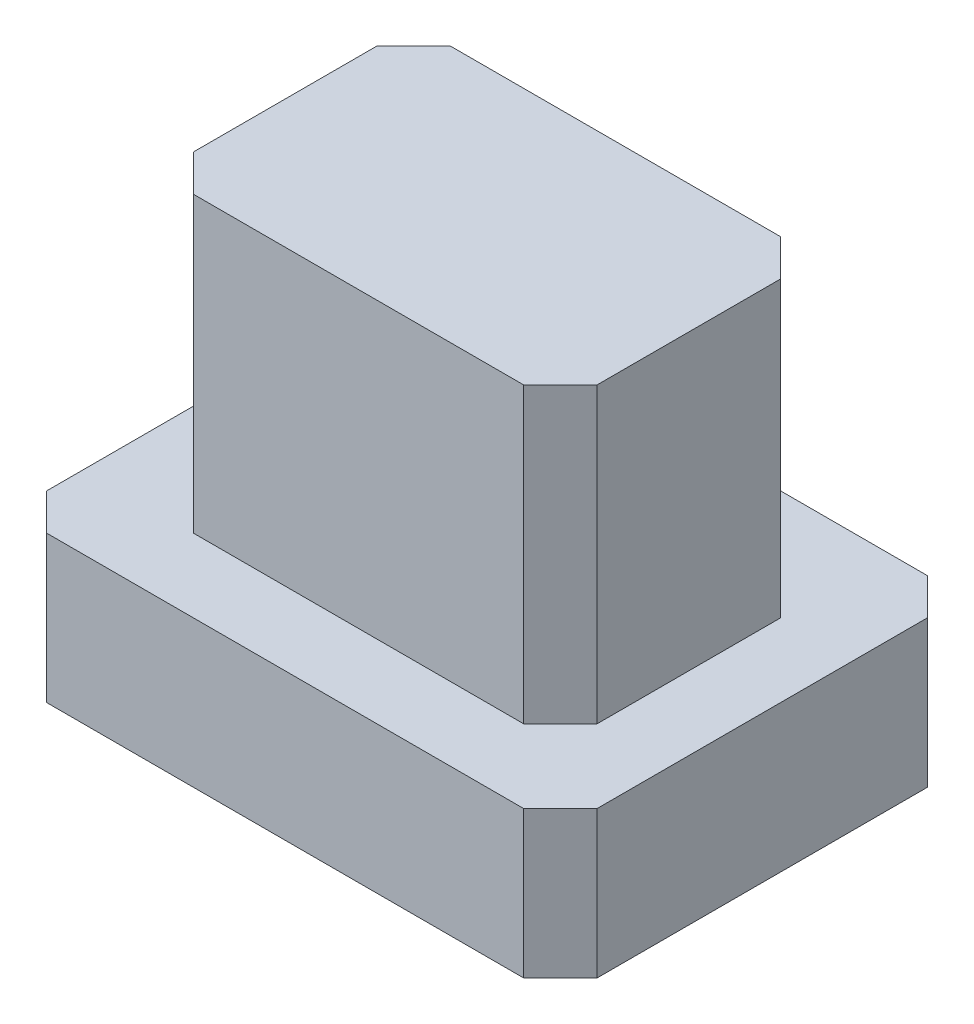
SolidWorks part; units mm, degrees
ref_plane "Plan de face" through (0, 0, 0) normal (0, 0, 1) x (1, 0, 0)
ref_plane "Plan de dessus" through (0, 0, 0) normal (0, 1, 0) x (1, 0, 0)
ref_plane "Plan de droite" through (0, 0, 0) normal (1, 0, 0) x (0, 0, -1)
sketch "Esquisse1" plane through (0, 0, 0) normal (0, 1, 0) x (1, 0, 0)
  line L1 (-7.5, -5.5) -> (7.5, -5.5)
  line L2 (-7.5, -5.5) -> (-7.5, 5.5)
  line L3 (-7.5, 5.5) -> (7.5, 5.5)
  line L4 (7.5, -5.5) -> (7.5, 5.5)
  line L5 (-7.5, -5.5) -> (7.5, 5.5) construction
  line L6 (-7.5, 5.5) -> (7.5, -5.5) construction
  point P0 (0, 0)
  dimension "D1" = 15
  dimension "D2" = 11
extrude "Boss.-Extru.1" add sketch "Esquisse1" against normal blind 4
chamfer "Chanfrein1" distance 1 angle 45 4 edges at (-7.5, -2, -5.5) (-7.5, -2, 5.5) (7.5, -2, -5.5) (7.5, -2, 5.5)
sketch "Esquisse2" plane through (0, 0, 0) normal (0, 1, 0) x (1, 0, 0)
  line L0 (-7.5, 4.5) -> (-7.5, -4.5) construction
  line L1 (-5.5, -3.5) -> (5.5, -3.5)
  line L2 (-5.5, -3.5) -> (-5.5, 3.5)
  line L3 (-5.5, 3.5) -> (5.5, 3.5)
  line L4 (5.5, -3.5) -> (5.5, 3.5)
  line L5 (-5.5, -3.5) -> (5.5, 3.5) construction
  line L6 (-5.5, 3.5) -> (5.5, -3.5) construction
  line L7 (6.5, 5.5) -> (-6.5, 5.5) construction
  point P0 (0, 0)
  dimension "D1" = 2
  dimension "D2" = 2
extrude "Boss.-Extru.2" add sketch "Esquisse2" along normal blind 8
chamfer "Chanfrein3" distance 1 angle 45 4 edges at (5.5, 4, 3.5) (5.5, 4, -3.5) (-5.5, 4, 3.5) (-5.5, 4, -3.5)
